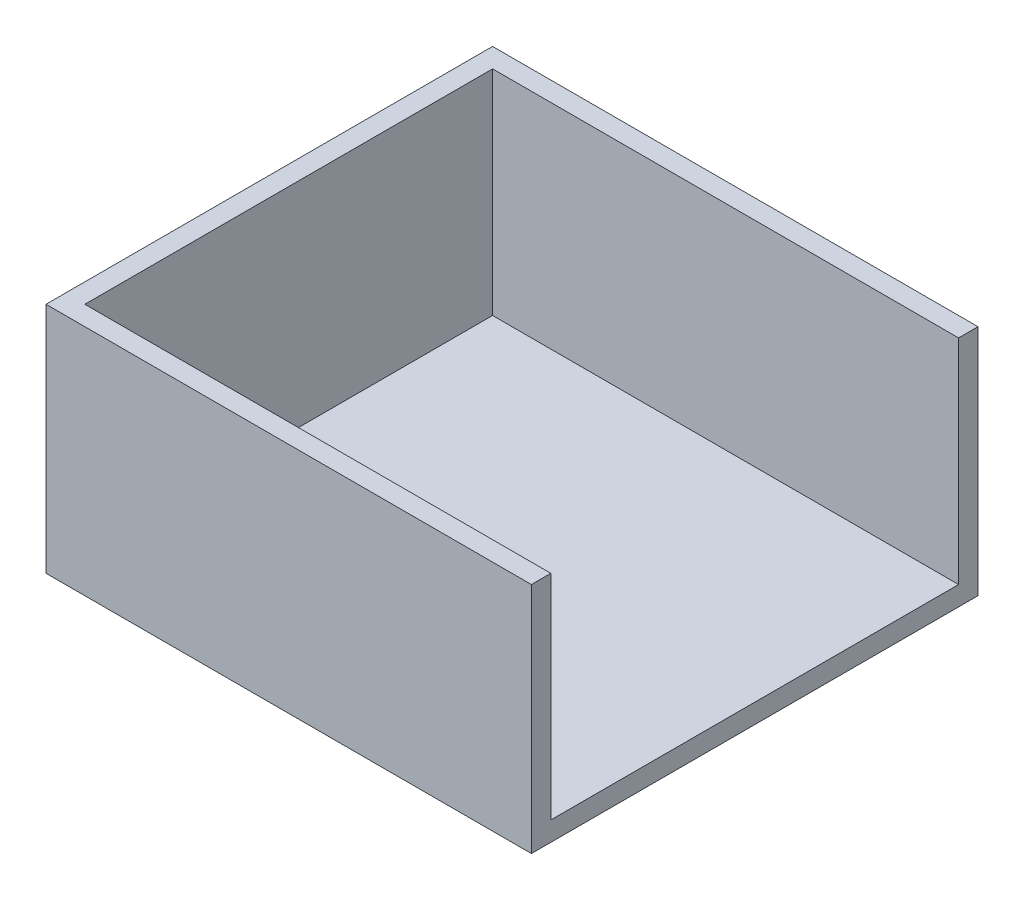
SolidWorks part; units mm, degrees
ref_plane "정면" through (0, 0, 0) normal (0, 0, 1) x (1, 0, 0)
ref_plane "윗면" through (0, 0, 0) normal (0, 1, 0) x (1, 0, 0)
ref_plane "우측면" through (0, 0, 0) normal (1, 0, 0) x (0, 0, -1)
sketch "스케치1" plane through (0, 0, 0) normal (0, 1, 0) x (1, 0, 0)
  line L1 (12.5, -11.5) -> (-12.5, -11.5)
  line L2 (12.5, -11.5) -> (12.5, 11.5)
  line L3 (12.5, 11.5) -> (-12.5, 11.5)
  line L4 (-12.5, -11.5) -> (-12.5, 11.5)
  line L5 (12.5, -11.5) -> (-12.5, 11.5) construction
  line L6 (12.5, 11.5) -> (-12.5, -11.5) construction
  point P0 (0, 0)
  dimension "D1" = 25
  dimension "D2" = 23
extrude "보스-돌출1" add sketch "스케치1" along normal blind 12
sketch "스케치2" plane through (0, 0, 0) normal (0, 1, 0) x (1, 0, 0)
  line L0 (12.5, 11.5) -> (-12.5, 11.5) construction
  line L1 (-11.5, 10.5) -> (13.5, 10.5)
  line L2 (-11.5, 10.5) -> (-11.5, -10.5)
  line L3 (-11.5, -10.5) -> (13.5, -10.5)
  line L4 (13.5, 10.5) -> (13.5, -10.5)
  line L5 (-12.5, 11.5) -> (-12.5, -11.5) construction
  dimension "D1" = 1
  dimension "D2" = 21
  dimension "D3" = 25
  dimension "D4" = 1
extrude "컷-돌출1" cut sketch "스케치2" along normal blind 11 from offset 1
sketch "스케치6" plane through (0, 0, 0) normal (0, 1, 0) x (1, 0, 0)
  line L1 (12.5, -11.5) -> (-12.5, -11.5)
  line L2 (12.5, -11.5) -> (12.5, 11.5)
  line L3 (12.5, 11.5) -> (-12.5, 11.5)
  line L4 (-12.5, -11.5) -> (-12.5, 11.5)
  line L5 (12.5, -11.5) -> (-12.5, 11.5) construction
  line L6 (12.5, 11.5) -> (-12.5, -11.5) construction
  point P0 (0, 0)
extrude "보스-돌출3" add sketch "스케치6" along normal blind 1 from offset 12 separate body
sketch "스케치8" plane through (0, 0, 0) normal (0, 1, 0) x (1, 0, 0)
  line L0 (-12.5, 11.5) -> (-12.5, -11.5) construction
  line L2 (-12.5, -11.5) -> (12.5, -11.5) construction
  circle A0 centre (-0.75, 0) radius 9.75
  dimension "D1" = 2
  dimension "D2" = 19.5
  dimension "D3" = 1.75
extrude "컷-돌출2" cut sketch "스케치8" against normal blind 1 from surface at 13 starting at face at (0, 13, 0)
sketch "스케치9" plane through (0, 13, 0) normal (0, 1, 0) x (1, 0, 0)
  line L4 (-12.5, 11.5) -> (-12.5, -11.5)
  line L5 (-12.5, -11.5) -> (12.5, -11.5)
  line L6 (12.5, -11.5) -> (12.5, 11.5)
  line L7 (12.5, 11.5) -> (-12.5, 11.5)
  line L8 (-12.5, 11.5) -> (-12.5, -11.5)
  line L9 (-12.5, -11.5) -> (12.5, -11.5)
  line L10 (12.5, -11.5) -> (12.5, 11.5)
  line L11 (12.5, 11.5) -> (-12.5, 11.5)
  dimension "D1" = 0
extrude "컷-돌출3" cut sketch "스케치9" against normal blind 1
